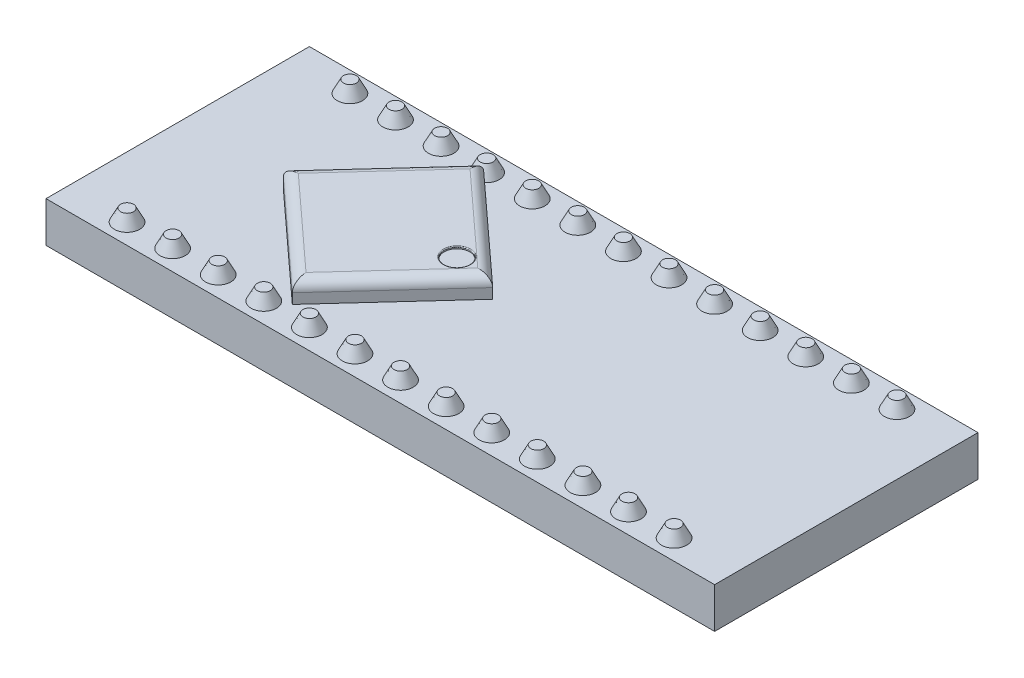
SolidWorks part; units mm, degrees
ref_plane "Front Plane" through (0, 0, 0) normal (0, 0, 1) x (1, 0, 0)
ref_plane "Top Plane" through (0, 0, 0) normal (0, 1, 0) x (1, 0, 0)
ref_plane "Right Plane" through (0, 0, 0) normal (1, 0, 0) x (0, 0, -1)
sketch "Sketch1" plane through (0, 0, 0) normal (0, 1, 0) x (1, 0, 0)
  line L1 (-16.5, 6.5) -> (16.5, 6.5)
  line L2 (-16.5, 6.5) -> (-16.5, -6.5)
  line L3 (-16.5, -6.5) -> (16.5, -6.5)
  line L4 (16.5, 6.5) -> (16.5, -6.5)
  line L5 (-16.5, 6.5) -> (16.5, -6.5) construction
  line L6 (-16.5, -6.5) -> (16.5, 6.5) construction
  point P0 (0, 0)
  dimension "D1" = 13
  dimension "D2" = 33
extrude "Boss-Extrude1" add sketch "Sketch1" along normal blind 2
sketch "Sketch2" plane through (0, 2, 0) normal (0, 1, 0) x (1, 0, 0)
  line L0 (-11.0637, -0.2218) -> (-5.8971, -4.9448)
  line L1 (-11.0637, -0.2218) -> (-6.3407, 4.9448)
  line L2 (-5.8971, -4.9448) -> (-1.1741, 0.2218)
  line L3 (-6.3407, 4.9448) -> (-1.1741, 0.2218)
  line L4 (-11.0637, -0.2218) -> (-1.1741, 0.2218) construction
  line L5 (-5.8971, -4.9448) -> (-6.3407, 4.9448) construction
  point P0 (0, 0)
  point P1 (-6.1189, 0)
  dimension "D1" = 7
  dimension "D2" = 7
extrude "Boss-Extrude2" add sketch "Sketch2" along normal blind 1
fillet "Fillet1" radius 0.5 4 edges at (-3.7574, 3, -2.5833) (-3.5356, 3, 2.3615) (-8.4804, 3, 2.5833) (-8.7022, 3, -2.3615)
sketch "Sketch3" plane through (0, 3, 0) normal (0, 1, 0) x (1, 0, 0)
  circle A0 centre (-2.8689, 0.1515) radius 0.6312
extrude "Cut-Extrude1" cut sketch "Sketch3" against normal blind 0.1
fillet "Fillet2" radius 0.04 1 edges at (-2.8689, 3, 0.4797)
sketch "Sketch4" plane through (0, 2, 0) normal (0, 1, 0) x (1, 0, 0)
  line L0 (16.5, 6.5) -> (-16.5, 6.5) construction
  line L1 (-16.5, 6.5) -> (-16.5, -6.5) construction
  line L3 (-55, 0) -> (55, 0) construction
  circle A0 centre (-13.5, 5.5) radius 0.625
  circle A1 centre (-11.25, 5.5) radius 0.625
  circle A2 centre (-9, 5.5) radius 0.625
  circle A3 centre (-6.75, 5.5) radius 0.625
  circle A4 centre (-4.5, 5.5) radius 0.625
  circle A5 centre (-2.25, 5.5) radius 0.625
  circle A6 centre (0, 5.5) radius 0.625
  circle A7 centre (2.25, 5.5) radius 0.625
  circle A8 centre (4.5, 5.5) radius 0.625
  circle A9 centre (6.75, 5.5) radius 0.625
  circle A10 centre (9, 5.5) radius 0.625
  circle A11 centre (11.25, 5.5) radius 0.625
  circle A12 centre (13.5, 5.5) radius 0.625
  circle A13 centre (-13.5, -5.5) radius 0.625
  circle A14 centre (-11.25, -5.5) radius 0.625
  circle A15 centre (-9, -5.5) radius 0.625
  circle A16 centre (-6.75, -5.5) radius 0.625
  circle A17 centre (-4.5, -5.5) radius 0.625
  circle A18 centre (-2.25, -5.5) radius 0.625
  circle A19 centre (0, -5.5) radius 0.625
  circle A20 centre (2.25, -5.5) radius 0.625
  circle A21 centre (4.5, -5.5) radius 0.625
  circle A22 centre (6.75, -5.5) radius 0.625
  circle A23 centre (9, -5.5) radius 0.625
  circle A24 centre (11.25, -5.5) radius 0.625
  circle A25 centre (13.5, -5.5) radius 0.625
  dimension "D1" = 1
  dimension "D3" = 1.25
  dimension "D2" = 3
  dimension "D4" = 13
  dimension "D5" = 13
extrude "Boss-Extrude3" add sketch "Sketch4" along normal blind 0.6 draft 27 contours A0 | A1 | A2 | A3 | A4 | A5 | A6 | A7 | A8 | A9 | A10 | A11 | A12 | A25 | A24 | A23 | A22 | A21 | A20 | A19 | A18 | A17 | A16 | A15 | A13 | A14
sketch "Sketch6" plane through (0, 3, 0) normal (0, 1, 0) x (1, 0, 0)
  spline S0 degree 1 poles (-7.437, -2.4519) (-7.5994, 1.7699) knots 0 0 1 1
  text T0 "Atmega32" font "Century Gothic" height 0.6
  dimension "D1" = 1.8805
  dimension "D2" = 5.5564
  dimension "D3" = 5.7188
  dimension "D4" = 2.4684
  dimension "D5" = 4.2384
  dimension "D6" = 6.6903
